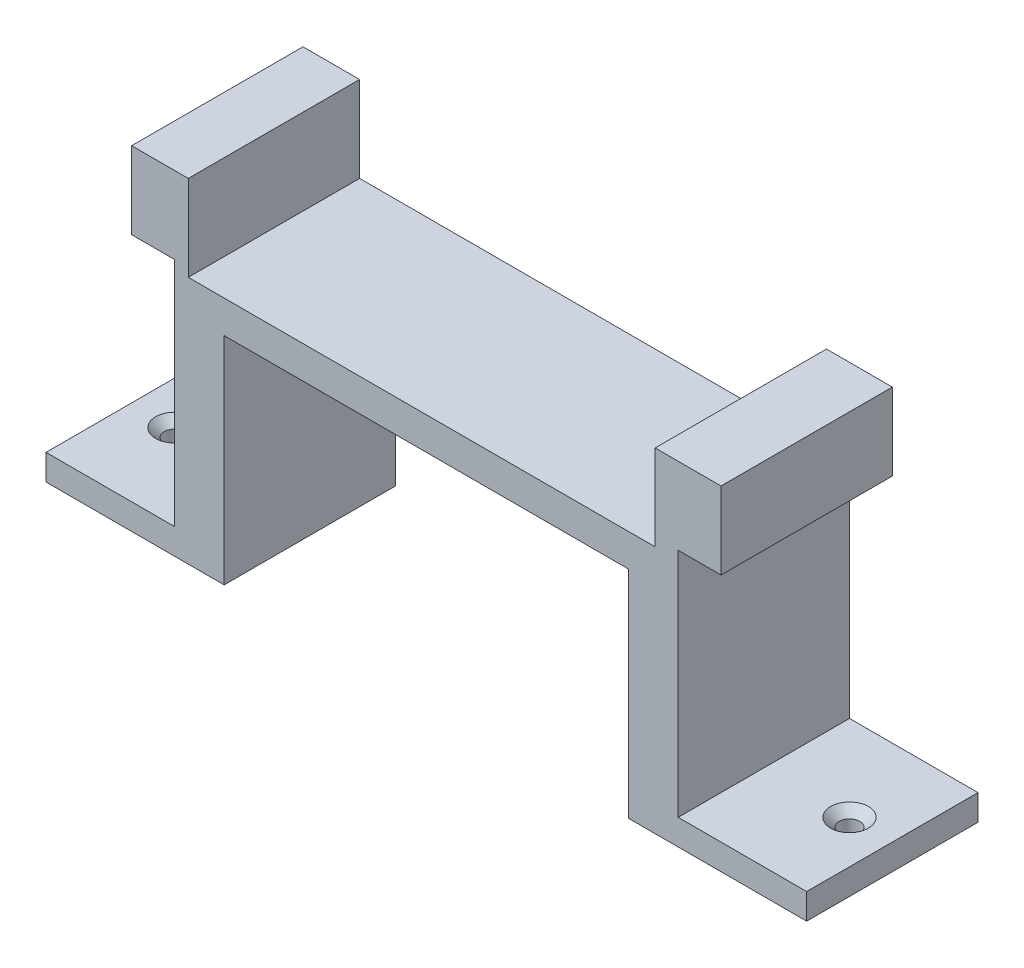
SolidWorks part; units mm, degrees
ref_plane "Front Plane" through (0, 0, 0) normal (0, 0, 1) x (1, 0, 0)
ref_plane "Top Plane" through (0, 0, 0) normal (0, 1, 0) x (1, 0, 0)
ref_plane "Right Plane" through (0, 0, 0) normal (1, 0, 0) x (0, 0, -1)
sketch "Sketch1" plane through (0, 0, 0) normal (0, 0, 1) x (1, 0, 0)
  line L1 (-34.4, 19.5) -> (34.4, 19.5)
  line L2 (-34.4, 19.5) -> (-34.4, -19.5)
  line L3 (-34.4, -19.5) -> (34.4, -19.5)
  line L4 (34.4, 19.5) -> (34.4, -19.5)
  line L5 (-34.4, 19.5) -> (34.4, -19.5) construction
  line L6 (-34.4, -19.5) -> (34.4, 19.5) construction
  point P0 (0, 0)
  dimension "D1" = 39
  dimension "D2" = 68.8
extrude "Boss-Extrude1" add sketch "Sketch1" along normal blind 20
sketch "Sketch2" plane through (0, 0, 20) normal (0, 0, 1) x (1, 0, 0)
  line L0 (-34.4, -19.5) -> (34.4, -19.5) construction
  line L1 (-23.6, -19.5) -> (23.6, -19.5)
  line L2 (-23.6, -19.5) -> (-23.6, 5.7)
  line L3 (-23.6, 5.7) -> (23.6, 5.7)
  line L4 (23.6, -19.5) -> (23.6, 5.7)
  line L5 (34.4, 19.5) -> (-34.4, 19.5) construction
  line L6 (-27.79, 19.5) -> (26.71, 19.5)
  line L7 (-27.79, 19.5) -> (-27.79, 9.5)
  line L8 (-27.79, 9.5) -> (26.71, 9.5)
  line L9 (26.71, 19.5) -> (26.71, 9.5)
  dimension "D1" = 25.2
  dimension "D2" = 47.2
  dimension "D3" = 54.5
  dimension "D4" = 10
  dimension "D5" = 23.6
  dimension "D6" = 26.71
extrude "Cut-Extrude1" cut sketch "Sketch2" against normal blind 50
sketch "Sketch3" plane through (0, 0, 20) normal (0, 0, 1) x (1, 0, 0)
  line L1 (-34.4, -19.5) -> (-29.4, -19.5)
  line L2 (-34.4, -19.5) -> (-34.4, 10.5)
  line L3 (-34.4, 10.5) -> (-29.4, 10.5)
  line L4 (-29.4, -19.5) -> (-29.4, 10.5)
  line L5 (34.4, -19.5) -> (29.4, -19.5)
  line L6 (34.4, -19.5) -> (34.4, 10.5)
  line L7 (34.4, 10.5) -> (29.4, 10.5)
  line L8 (29.4, -19.5) -> (29.4, 10.5)
  dimension "D1" = 5
  dimension "5" = 5
  dimension "D3" = 30
  dimension "D4" = 30
extrude "Cut-Extrude2" cut sketch "Sketch3" against normal blind 50
sketch "Sketch4" plane through (-29.4, 0, 0) normal (-1, 0, 0) x (0, 0, 1)
  line L0 (20, -19.5) -> (20, 10.5) construction
  line L1 (0, -19.5) -> (20, -19.5)
  line L2 (0, -19.5) -> (0, -16.5)
  line L3 (0, -16.5) -> (20, -16.5)
  line L4 (20, -19.5) -> (20, -16.5)
  dimension "D1" = 3
extrude "Boss-Extrude2" add sketch "Sketch4" along normal blind 15
sketch "Sketch5" plane through (29.4, 0, 0) normal (1, 0, 0) x (0, 0, -1)
  line L0 (0, 10.5) -> (0, -19.5) construction
  line L1 (-20, -19.5) -> (0, -19.5)
  line L2 (-20, -19.5) -> (-20, -16.5)
  line L3 (-20, -16.5) -> (0, -16.5)
  line L4 (0, -19.5) -> (0, -16.5)
  dimension "D1" = 3
extrude "Boss-Extrude3" add sketch "Sketch5" along normal blind 15
sketch "Sketch8" plane through (0, -16.5, 0) normal (0, 1, 0) x (1, 0, 0)
  line L0 (-44.4, -20) -> (-44.4, 0) construction
  line L1 (-44.4, -20) -> (-29.4, -20) construction
  point P0 (-39.4, -10)
  point P2 (-39.4, -10)
  point P5 (-39.4, -10)
  dimension "D1" = 5
  dimension "D2" = 10
hole_wizard "CSK for M2 Flat Head Machine Screw1" positions "Sketch8" profile "Sketch7" countersink size "M2" standard "ANSI Metric" end condition through all
sketch "Sketch7" plane through (-39.4, -16.5, 10) normal (1, 0, 0) x (0, 0, 1)
  line L0 (0, 0) -> (0, 3)
  line L1 (0, 3) -> (1.2, 3)
  line L2 (1.2, 3) -> (1.2, 1)
  line L3 (1.2, 1) -> (2.2, 0)
  line L5 (2.2, 0) -> (0, 0)
  line L6 (-1.2, 1) -> (-2.2, 0) construction
  line L11 (0, -6.35) -> (0, 107.95) construction
  dimension "Thru Hole Dia." = 2.4
  dimension "Thru Hole Depth" = 3
  dimension "Near C'Sink Dia." = 4.4
  dimension "Near C'Sink Angle" = 90
sketch "Sketch11" plane through (0, -16.5, 0) normal (0, 1, 0) x (1, 0, 0)
  line L0 (44.4, 0) -> (44.4, -20) construction
  line L1 (44.4, -20) -> (29.4, -20) construction
  point P0 (39.4, -10)
  dimension "D1" = 5
  dimension "D2" = 10
hole_wizard "CSK for M2 Flat Head Machine Screw2" positions "Sketch11" profile "Sketch10" countersink size "M2" standard "ANSI Metric" end condition through all
sketch "Sketch10" plane through (39.4, -16.5, 10) normal (1, 0, 0) x (0, 0, 1)
  line L0 (0, 0) -> (0, 3)
  line L1 (0, 3) -> (1.2, 3)
  line L2 (1.2, 3) -> (1.2, 1)
  line L3 (1.2, 1) -> (2.2, 0)
  line L5 (2.2, 0) -> (0, 0)
  line L6 (-1.2, 1) -> (-2.2, 0) construction
  line L11 (0, -6.35) -> (0, 107.95) construction
  dimension "Thru Hole Dia." = 2.4
  dimension "Thru Hole Depth" = 3
  dimension "Near C'Sink Dia." = 4.4
  dimension "Near C'Sink Angle" = 90
